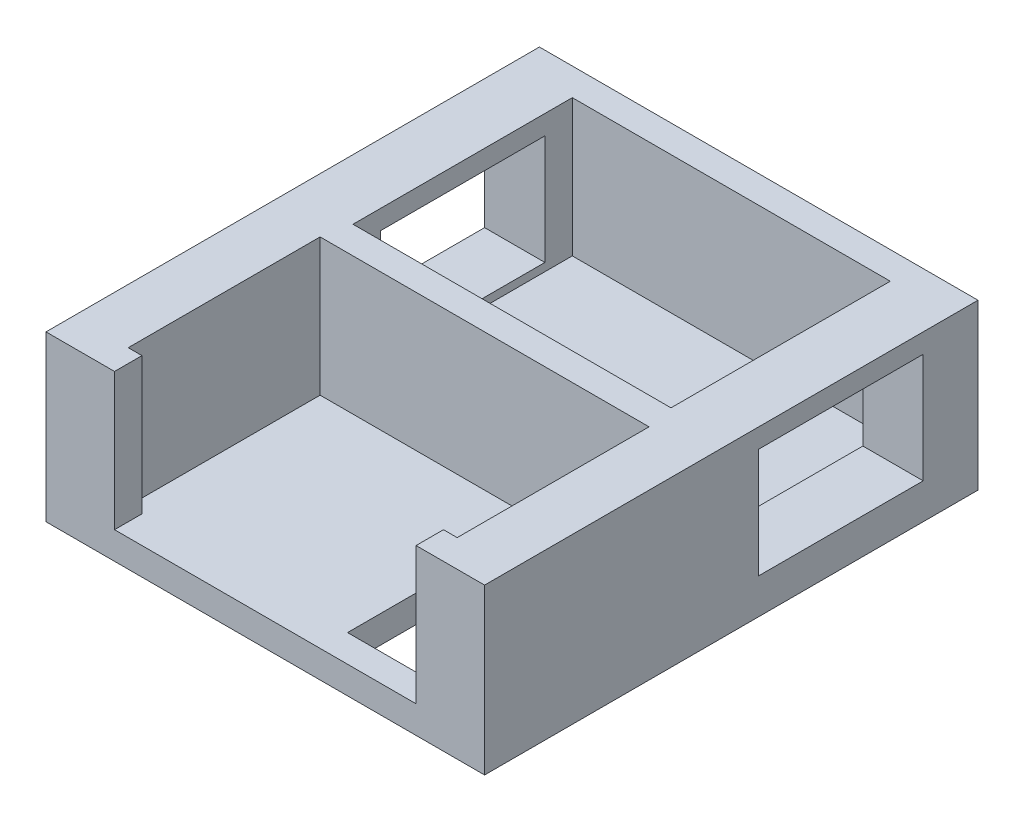
SolidWorks part; units mm, degrees
material "ABS"
ref_plane "Front Plane" through (0, 0, 0) normal (0, 0, 1) x (1, 0, 0)
ref_plane "Top Plane" through (0, 0, 0) normal (0, 1, 0) x (1, 0, 0)
ref_plane "Right Plane" through (0, 0, 0) normal (1, 0, 0) x (0, 0, -1)
sketch "Sketch2" plane through (0, 0, 0) normal (0, 1, 0) x (1, 0, 0)
  line L1 (-37.6471, 14.2876) -> (42.3529, 14.2876)
  line L2 (-37.6471, 14.2876) -> (-37.6471, -85.7124)
  line L3 (-37.6471, -85.7124) -> (42.3529, -85.7124)
  line L4 (42.3529, 14.2876) -> (42.3529, -85.7124)
  circle A0 centre (16.3529, -25.7124) radius 10
  dimension "D7" = 20
  dimension "D1" = 80
  dimension "D2" = 100
  dimension "D3" = 60
extrude "camera lense" add sketch "Sketch2" along normal blind 5
sketch "Sketch3" plane through (0, 5, 0) normal (0, 1, 0) x (1, 0, 0)
  line L1 (-26.6471, -0.7124) -> (31.3529, -0.7124)
  line L2 (-26.6471, -0.7124) -> (-26.6471, -40.7124)
  line L3 (-26.6471, -40.7124) -> (31.3529, -40.7124)
  line L4 (31.3529, -0.7124) -> (31.3529, -40.7124)
  line L5 (-37.6471, 14.2876) -> (42.3529, 14.2876)
  line L6 (-37.6471, 14.2876) -> (-37.6471, -85.7124)
  line L7 (-37.6471, -85.7124) -> (42.3529, -85.7124)
  line L8 (42.3529, 14.2876) -> (42.3529, -85.7124)
  line L9 (32.3529, -45.7124) -> (-27.6471, -45.7124)
  line L10 (32.3529, -45.7124) -> (32.3529, -80.7124)
  line L11 (32.3529, -80.7124) -> (-27.6471, -80.7124)
  line L12 (-27.6471, -45.7124) -> (-27.6471, -80.7124)
  circle A0 centre (16.3529, -25.7124) radius 10 construction
  dimension "D3" = 15
  dimension "D4" = 15
  dimension "D9" = 40
  dimension "D1" = 58
  dimension "D2" = 40
  dimension "D5" = 60
  dimension "D6" = 35
  dimension "D7" = 5
  dimension "D8" = 10
  dimension "D10" = 100
  dimension "D11" = 80
extrude "camera" add sketch "Sketch3" along normal blind 25
sketch "Sketch4" plane through (0, 0, -14.2876) normal (0, 0, -1) x (-1, 0, 0)
  line L0 (-42.3529, 30) -> (-42.3529, 0) construction
  line L1 (-41.3529, 28.9797) -> (36.6471, 28.9797)
  line L2 (-41.3529, 28.9797) -> (-41.3529, 1)
  line L3 (-41.3529, 1) -> (36.6471, 1)
  line L4 (36.6471, 28.9797) -> (36.6471, 1)
  line L5 (74.3596, 0) -> (-74.3596, 0) construction
  dimension "D1" = 78
  dimension "D2" = 1
  dimension "D3" = 1
extrude "hollow top" cut sketch "Sketch4" against normal offset from surface (8 mm away) 5 from offset 2 up to face at (2.3529, 17.5, 0.7124) offset against normal yes
sketch "Sketch10" plane through (0, 30, 0) normal (0, 1, 0) x (1, 0, 0)
  line L0 (42.3529, -85.7124) -> (42.3529, 14.2876) construction
  line L1 (-37.6471, 14.2876) -> (42.3529, 14.2876)
  line L2 (-37.6471, 14.2876) -> (-37.6471, 4.2876)
  line L3 (-37.6471, 4.2876) -> (42.3529, 4.2876)
  line L4 (42.3529, 14.2876) -> (42.3529, 4.2876)
  dimension "D1" = 10
extrude "Cut-Extrude4" cut sketch "Sketch10" against normal through all
sketch "Sketch11" plane through (42.3529, 0, 0) normal (1, 0, 0) x (0, 0, -1)
  line L0 (4.2876, 0) -> (4.2876, 30) construction
  line L1 (-35.7124, 26.4658) -> (-5.7124, 26.4658)
  line L2 (-35.7124, 26.4658) -> (-35.7124, 6.4658)
  line L3 (-35.7124, 6.4658) -> (-5.7124, 6.4658)
  line L4 (-5.7124, 26.4658) -> (-5.7124, 6.4658)
  dimension "D1" = 30
  dimension "D2" = 20
  dimension "D3" = 10
extrude "Cut-Extrude5" cut sketch "Sketch11" against normal through all
sketch "Sketch12" plane through (0, 5, 0) normal (0, 1, 0) x (1, 0, 0)
  line L0 (32.3529, -80.7124) -> (32.3529, -45.7124) construction
  line L1 (32.3529, -45.7124) -> (12.3529, -45.7124)
  line L2 (32.3529, -45.7124) -> (32.3529, -80.7124)
  line L3 (32.3529, -80.7124) -> (12.3529, -80.7124)
  line L4 (12.3529, -45.7124) -> (12.3529, -80.7124)
  line L5 (32.3529, -80.7124) -> (32.3529, -45.7124) construction
  line L6 (-27.6471, -80.7124) -> (32.3529, -80.7124) construction
  line L7 (-27.6471, -45.7124) -> (-27.6471, -80.7124) construction
  line L9 (32.3529, -45.7124) -> (-27.6471, -45.7124) construction
  dimension "D1" = 40
extrude "Cut-Extrude6" cut sketch "Sketch12" against normal through all
sketch "Sketch13" plane through (0, 0, 85.7124) normal (0, 0, 1) x (1, 0, 0)
  line L0 (-37.6471, 30) -> (42.3529, 30) construction
  line L1 (29.8529, 30) -> (-25.1471, 30)
  line L2 (29.8529, 30) -> (29.8529, 5)
  line L3 (29.8529, 5) -> (-25.1471, 5)
  line L4 (-25.1471, 30) -> (-25.1471, 5)
  line L7 (-37.6471, 30) -> (-37.6471, 0) construction
  line L10 (-37.6471, 0) -> (42.3529, 0) construction
  dimension "D1" = 55
  dimension "D2" = 12.5
  dimension "D3" = 5
extrude "Cut-Extrude7" cut sketch "Sketch13" against normal blind 10
